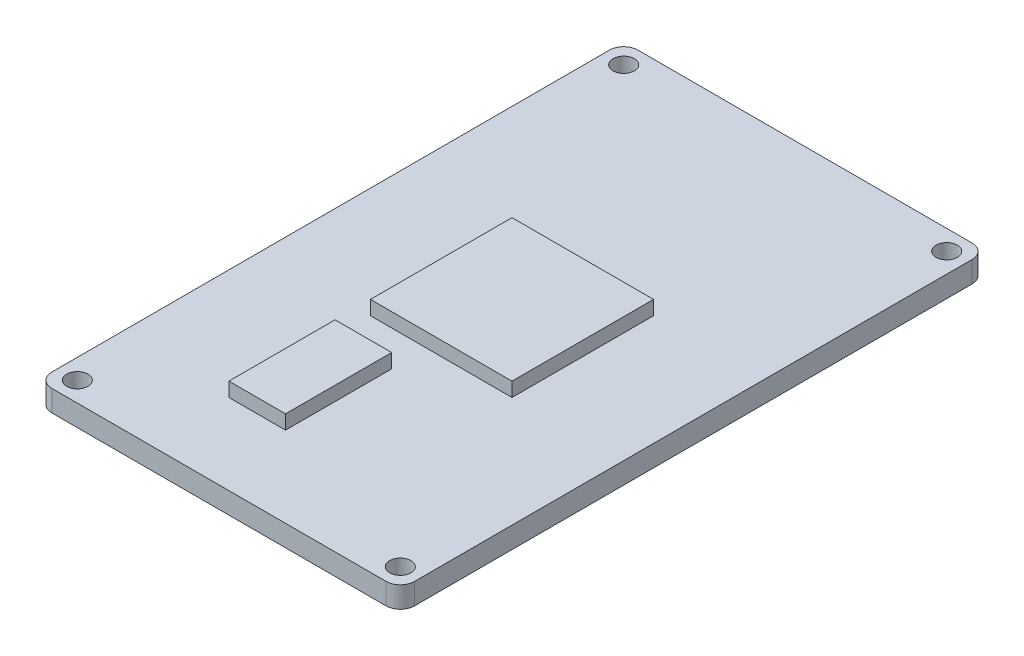
SolidWorks part; units mm, degrees
ref_plane "前视基准面" through (0, 0, 0) normal (0, 0, 1) x (1, 0, 0)
ref_plane "上视基准面" through (0, 0, 0) normal (0, 1, 0) x (1, 0, 0)
ref_plane "右视基准面" through (0, 0, 0) normal (1, 0, 0) x (0, 0, -1)
sketch "草图1" plane through (0, 0, 0) normal (0, 1, 0) x (1, 0, 0)
  line L0 (0, 0) -> (0, 36.41) construction
  line L1 (-25.62, -41.4) -> (25.62, -41.4)
  line L2 (-25.62, -41.4) -> (-25.62, 41.4)
  line L3 (-25.62, 41.4) -> (25.62, 41.4)
  line L4 (25.62, -41.4) -> (25.62, 41.4)
  line L5 (-25.62, -41.4) -> (25.62, 41.4) construction
  line L6 (-25.62, 41.4) -> (25.62, -41.4) construction
  line L7 (0, 0) -> (34.8102, 0) construction
  circle A0 centre (22.82, 38.6) radius 1.5
  circle A1 centre (-22.82, 38.6) radius 1.5
  circle A2 centre (-22.82, -38.6) radius 1.5
  circle A3 centre (22.82, -38.6) radius 1.5
  point P0 (0, 0)
  dimension "D4" = 3
  dimension "D1" = 51.24
  dimension "D2" = 82.8
  dimension "D3" = 45.64
  dimension "D5" = 77.2
extrude "凸台-拉伸1" add sketch "草图1" along normal blind 3 contours L4 L3 L2 L1 | A0 | A1 | A2 | A3
sketch "草图2" plane through (0, 3, 0) normal (0, 1, 0) x (1, 0, 0)
  line L1 (-10, 10) -> (10, 10)
  line L2 (-10, 10) -> (-10, -10)
  line L3 (-10, -10) -> (10, -10)
  line L4 (10, 10) -> (10, -10)
  line L5 (-10, 10) -> (10, -10) construction
  line L6 (-10, -10) -> (10, 10) construction
  line L10 (0, 0) -> (0, 50.1662) construction
  line L11 (0, 0) -> (74.4117, 0) construction
  line L17 (-2, -15) -> (-10, -15)
  line L18 (-2, -15) -> (-2, -30)
  line L19 (-2, -30) -> (-10, -30)
  line L20 (-10, -15) -> (-10, -30)
  line L21 (-2, -15) -> (-10, -30) construction
  line L22 (-2, -30) -> (-10, -15) construction
  point P0 (0, 0)
  point P5 (-6, -22.5)
  dimension "D1" = 20
  dimension "D2" = 20
  dimension "D3" = 8
  dimension "D4" = 15
  dimension "D5" = 15
  dimension "D6" = 2
extrude "凸台-拉伸2" add sketch "草图2" along normal blind 2
fillet "圆角1" radius 2 4 edges at (-25.62, 1.5, -41.4) (25.62, 1.5, -41.4) (25.62, 1.5, 41.4) (-25.62, 1.5, 41.4)
